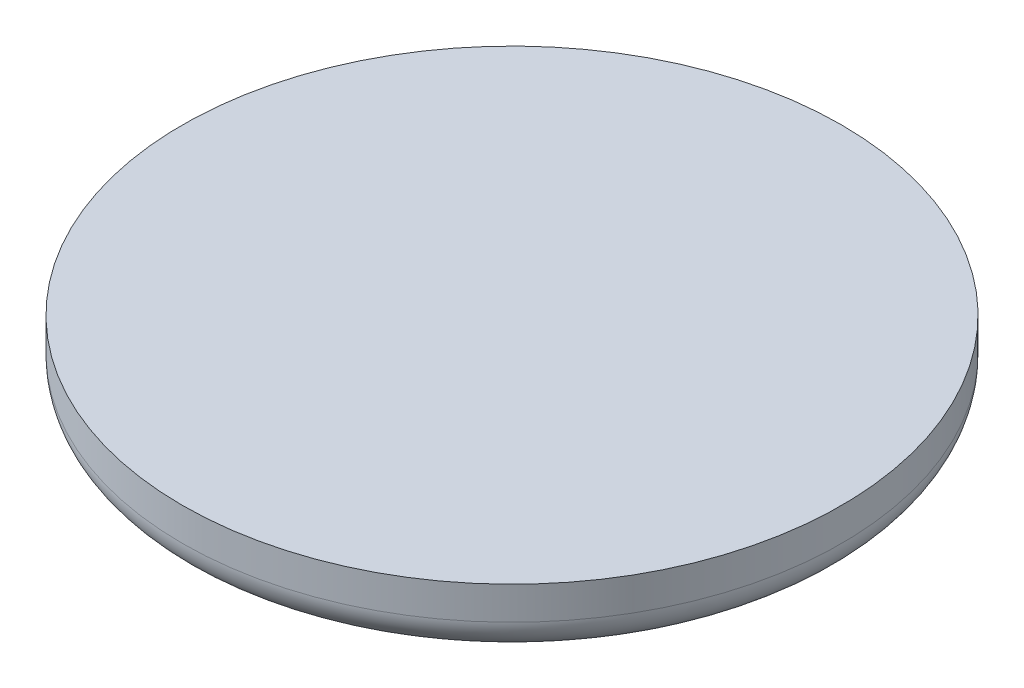
SolidWorks part; units mm, degrees
ref_plane "Front Plane" through (0, 0, 0) normal (1, 0, 0) x (0, 1, 0)
ref_plane "Top Plane" through (0, 0, 0) normal (0, 0, 1) x (0, 1, 0)
ref_plane "Right Plane" through (0, 0, 0) normal (0, 1, 0) x (-1, 0, 0)
sketch "Sketch1" plane through (0, 0, 0) normal (0, 1, 0) x (-1, 0, 0)
  circle A0 centre (0, 0) radius 15
extrude "Boss-Extrude1" add sketch "Sketch1" against normal blind 3
fillet "Fillet1" radius 1.5 1 edges at (0, -3, 15)
